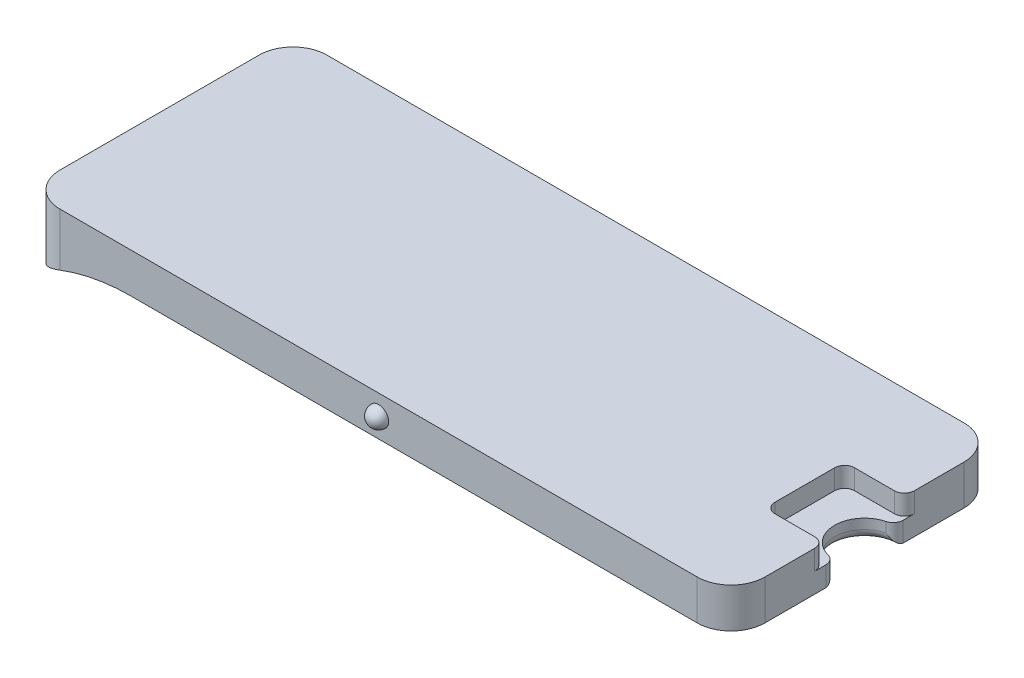
SolidWorks part; units mm, degrees
ref_plane "Ebene vorne" through (0, 0, 0) normal (0, 0, 1) x (1, 0, 0)
ref_plane "Ebene oben" through (0, 0, 0) normal (0, 1, 0) x (1, 0, 0)
ref_plane "Ebene rechts" through (0, 0, 0) normal (1, 0, 0) x (0, 0, -1)
sketch "Skizze1" plane through (0, 0, 0) normal (0, 1, 0) x (1, 0, 0)
  line L0 (2, 0.3) -> (34, 0.3)
  line L1 (2, 0) -> (34, 0) construction
  line L2 (0, 2) -> (0, 12) construction
  line L3 (2, 14) -> (34, 14) construction
  line L4 (36, 2) -> (36, 12) construction
  line L5 (35.7, 2) -> (35.7, 12)
  line L6 (2, 13.7) -> (34, 13.7)
  line L7 (0.3, 2) -> (0.3, 12)
  arc A0 (2, 14) -> (0, 12) centre (2, 12) ccw construction
  arc A1 (0, 2) -> (2, 0) centre (2, 2) ccw construction
  arc A2 (36, 2) -> (34, 0) centre (34, 2) cw construction
  arc A3 (36, 12) -> (34, 14) centre (34, 12) ccw construction
  arc A4 (35.7, 2) -> (34, 0.3) centre (34, 2) cw
  arc A5 (35.7, 12) -> (34, 13.7) centre (34, 12) ccw
  arc A6 (2, 13.7) -> (0.3, 12) centre (2, 12) ccw
  arc A7 (0.3, 2) -> (2, 0.3) centre (2, 2) ccw
  point P7 (0, 14)
  point P10 (0, 0)
  point P13 (36, 0)
  dimension "D3" = 2
  dimension "D1" = 14
  dimension "D2" = 36
  dimension "D4" = 0.3
extrude "Aufsatz-Linear austragen1" add sketch "Skizze1" along normal blind 6
sketch "Skizze2" plane through (0, 0, -13.7) normal (0, 0, -1) x (-1, 0, 0)
  line L0 (-115.5636, 4) -> (19.4364, 4) construction
  line L1 (4.4364, -6) -> (5.4364, -6)
  line L3 (-115.5636, 4) -> (-5.5636, 4)
  line L4 (-34, 0) -> (-2, 0) construction
  line L5 (-35.7, 4) -> (-5.5636, 4)
  line L6 (-35.7, 4) -> (-35.7, 0)
  line L7 (-35.7, 0) -> (2.4364, 0)
  line L9 (-35.7, 6) -> (-35.7, 0) construction
  arc A2 (5.4364, -6) -> (0.761, 3) centre (-5.5636, -6) ccw
  arc A3 (4.4364, -6) -> (-5.5636, 4) centre (-5.5636, -6) ccw
  arc A5 (2.4364, 0) -> (-5.5636, 4) centre (-5.5636, -6) ccw
  spline S1 degree 3 poles (699.0028, 718.8603) (50.8296, -54.4821) (27.7157, -3.2907) (-1.3358, 3.5326) (-1.8631, 3.6408) (-2.9168, 3.8169) (-3.4438, 3.8849) (-36.5438, 6.7519) (-81.203, -75.098) (847.2524, -518.1991) knots -13.345138 -13.345138 -13.345138 -13.345138 0.25 0.25 0.5 0.5 0.75 0.75 16.154386 16.154386 16.154386 16.154386 only from (0.761, 3) to (-5.5636, 4)
  dimension "D1" = 0
extrude "Schnitt-Linear austragen1" cut sketch "Skizze2" against normal through all
sketch "Skizze3" plane through (0, 0, -13.7) normal (0, 0, -1) x (-1, 0, 0)
  line L0 (-35.7, 5) -> (-0.3, 5) construction
  line L1 (-35.7, 6) -> (-35.7, 4) construction
  line L2 (-0.3, 6) -> (-0.3, 2.5026) construction
  line L3 (-18.5, 5) -> (-17.5, 5)
  arc A0 (-17.5, 5) -> (-18.5, 5) centre (-18, 5) ccw
  dimension "D1" = 1
revolve "Rotation1" add sketch "Skizze3" angle 360 about L0
sketch "Skizze4" plane through (0.3, 0, 0) normal (-1, 0, 0) x (0, 0, 1)
  line L0 (-7, 2.5026) -> (-7, 6) construction
  line L1 (-12, 2.5026) -> (-2, 2.5026) construction
  line L2 (-12, 6) -> (-2, 6) construction
  line L3 (-7, 3.7513) -> (-7, 4.7513)
  arc A0 (-7, 4.7513) -> (-7, 3.7513) centre (-7, 4.2513) ccw
  dimension "D1" = 1
revolve "Rotation2" add sketch "Skizze4" angle 360 about L0
ref_plane "Ebene1" through (0, 0, -7) normal (0, 0, -1) x (-1, 0, 0)
mirror "Spiegeln1" about plane through (0, 0, -7) normal (0, 0, -1) of "Rotation1"
sketch "Skizze5" plane through (0, 4, 0) normal (0, -1, 0) x (1, 0, 0)
  line L0 (35.7, -2) -> (35.7, -12) construction
  circle A0 centre (35.7, -7) radius 1.5
  dimension "D1" = 3
extrude "Schnitt-Linear austragen2" cut sketch "Skizze5" against normal through all
sketch "Skizze6" plane through (0, 6, 0) normal (0, 1, 0) x (1, 0, 0)
  line L0 (35.7, 8.5) -> (35.7, 12) construction
  line L1 (35.7, 9) -> (32.7, 9)
  line L2 (35.7, 9) -> (35.7, 5)
  line L3 (35.7, 5) -> (32.7, 5)
  line L4 (32.7, 9) -> (32.7, 5)
  line L5 (34.2, 7) -> (35.7, 7) construction
  line L6 (32.7, 7) -> (35.7, 7) construction
  arc A3 (35.7, 8.5) -> (35.7, 5.5) centre (35.7, 7) ccw construction
  dimension "D1" = 4
  dimension "D2" = 3
extrude "Schnitt-Linear austragen3" cut sketch "Skizze6" against normal blind 1
fillet "Verrundung2" radius 0.5 7 edges at (35.7, 5.5, -9) (35.7, 5.5, -5) (32.7, 5.5, -5) (32.7, 5.5, -9) (35.7, 4.5, -8.5) (35.7, 4.5, -5.5) (34.2, 4, -7)
